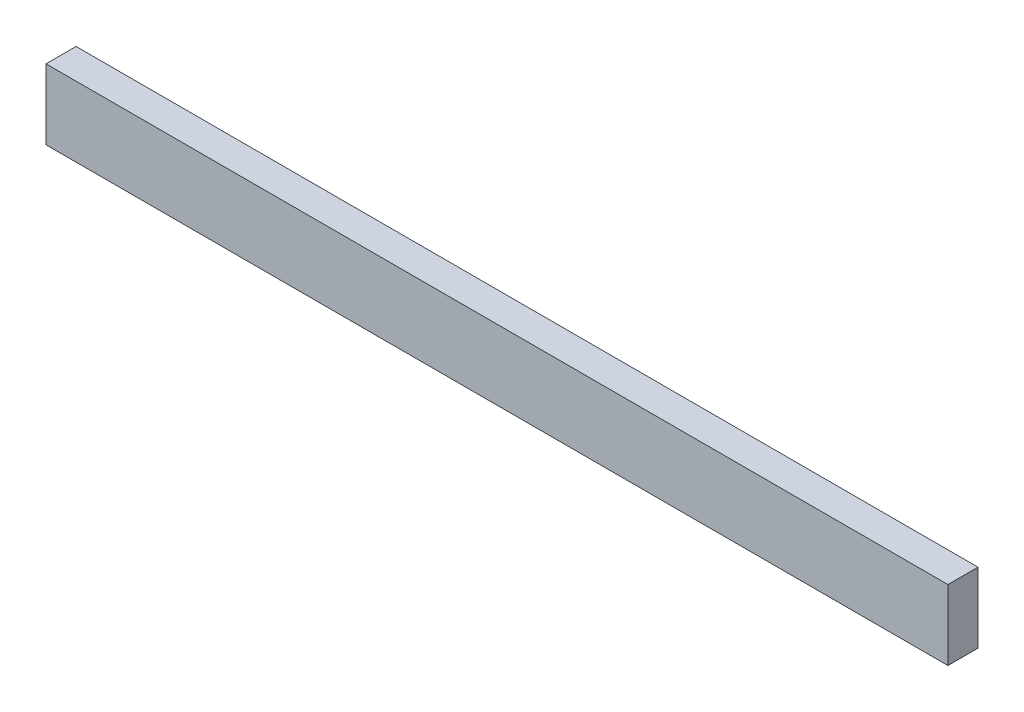
SolidWorks part; units mm, degrees
material "Pine"
ref_plane "Front Plane" through (0, 0, 0) normal (0, 0, 1) x (1, 0, 0)
ref_plane "Top Plane" through (0, 0, 0) normal (0, 1, 0) x (1, 0, 0)
ref_plane "Right Plane" through (0, 0, 0) normal (1, 0, 0) x (0, 0, -1)
sketch "Sketch1" plane through (0, 0, 0) normal (1, 0, 0) x (0, 0, -1)
  line L1 (-19.05, -44.45) -> (19.05, -44.45)
  line L2 (-19.05, -44.45) -> (-19.05, 44.45)
  line L3 (-19.05, 44.45) -> (19.05, 44.45)
  line L4 (19.05, -44.45) -> (19.05, 44.45)
  line L5 (-19.05, -44.45) -> (19.05, 44.45) construction
  line L6 (-19.05, 44.45) -> (19.05, -44.45) construction
  point P0 (0, 0)
  dimension "D1" = 88.9
  dimension "D2" = 38.1
extrude "Boss-Extrude1" add sketch "Sketch1" along normal blind 1143
